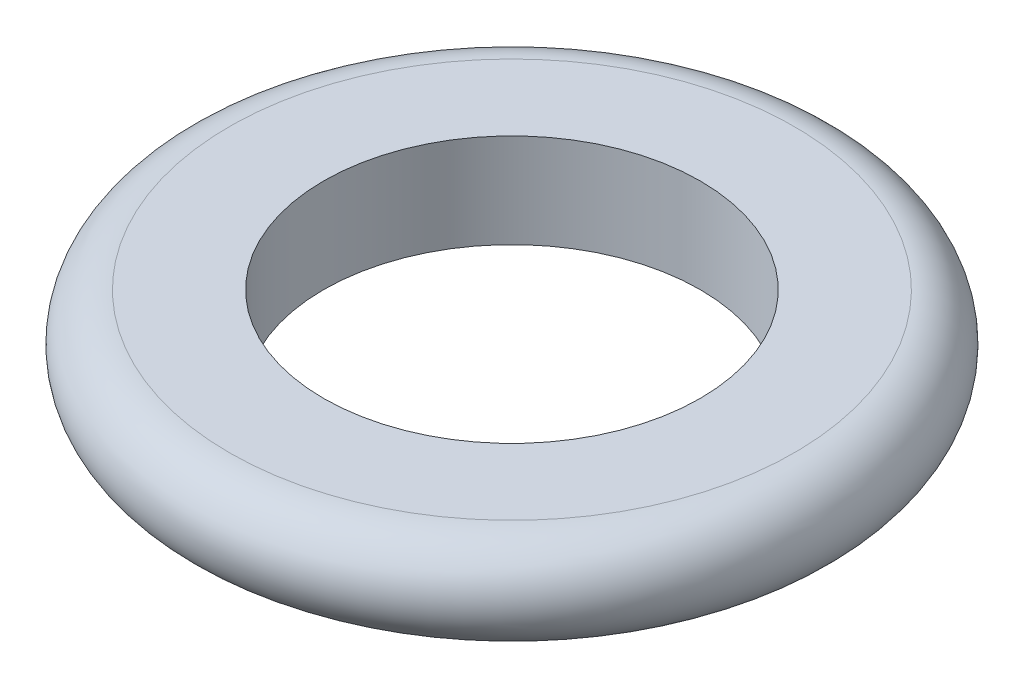
SolidWorks part; units mm, degrees
ref_plane "前视基准面" through (0, 0, 0) normal (0, 0, 1) x (1, 0, 0)
ref_plane "上视基准面" through (0, 0, 0) normal (0, 1, 0) x (1, 0, 0)
ref_plane "右视基准面" through (0, 0, 0) normal (1, 0, 0) x (0, 0, -1)
other "Configuration Table"
sketch "草图1" plane through (0, 0, 0) normal (0, 0, 1) x (1, 0, 0)
  line L0 (0, 3.5118) -> (0, -1.4961) construction
  line L1 (-4, 0) -> (-7, 0)
  line L2 (-7, 0) -> (-7, 1)
  line L3 (-7, 1) -> (-6, 1)
  line L4 (-6, 1) -> (-6, 3)
  line L5 (-6, 3) -> (-7, 3)
  line L6 (-7, 3) -> (-7, 4)
  line L7 (-7, 4) -> (-4, 4)
  line L8 (-4, 4) -> (-4, 0)
  line L9 (-6, 3) -> (-4, 3)
  line L10 (-4, 3) -> (-4, 1)
  line L11 (-4, 1) -> (-6, 1)
  circle A1 centre (-6, 2) radius 1
  dimension "D1" = 4
  dimension "D2" = 7
  dimension "D3" = 1
  dimension "D4" = 4
  dimension "D5" = 1
revolve "旋转1" add sketch "草图1" angle 360 about L0
